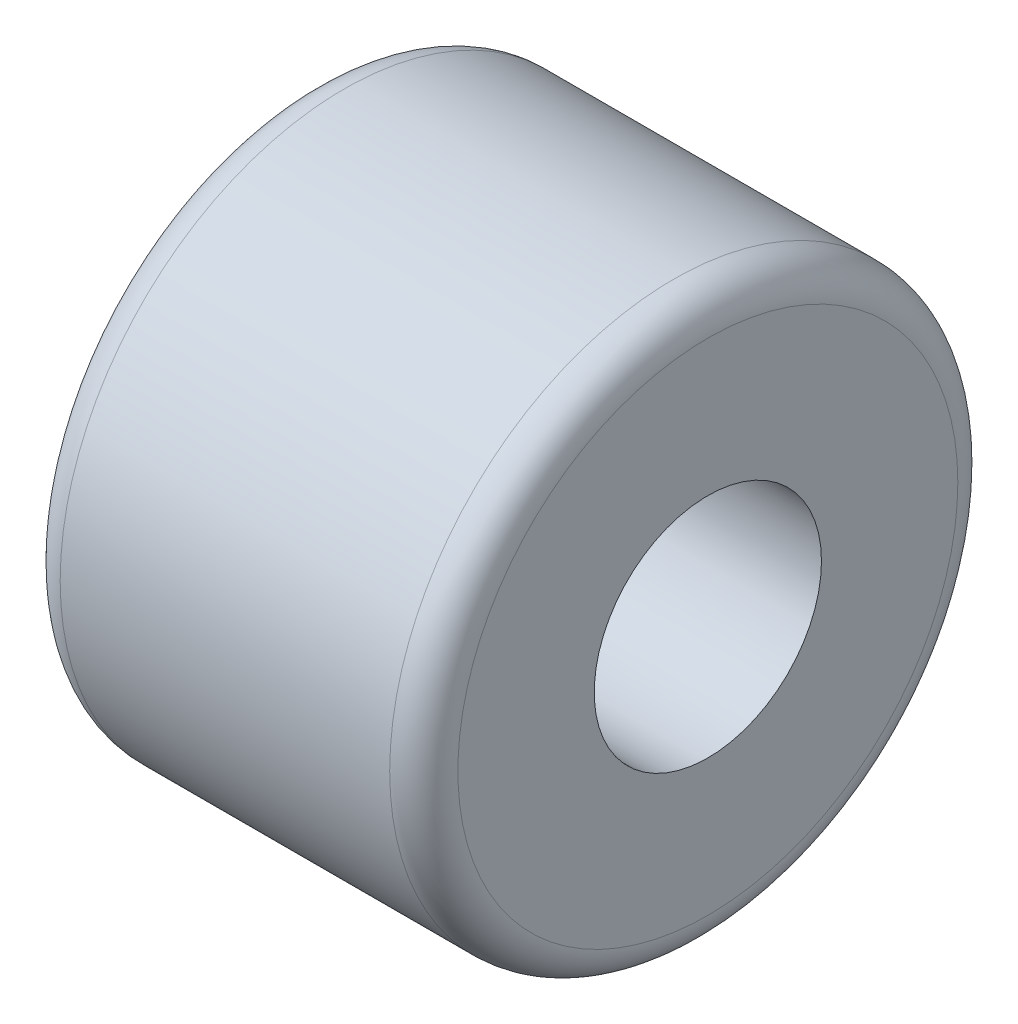
SolidWorks part; units mm, degrees
ref_plane "Front Plane" through (0, 0, 0) normal (1, 0, 0) x (0, 1, 0)
ref_plane "Top Plane" through (0, 0, 0) normal (0, 0, 1) x (0, 1, 0)
ref_plane "Right Plane" through (0, 0, 0) normal (0, 1, 0) x (-1, 0, 0)
sketch "Sketch1" plane through (0, 0, 0) normal (1, 0, 0) x (0, 1, 0)
  circle A0 centre (0, 0) radius 25
  circle A1 centre (0, 0) radius 1.5
  dimension "D1" = 50
  dimension "D2" = 3
extrude "Boss-Extrude1" add sketch "Sketch1" along normal blind 35
sketch "Sketch2" plane through (35, 0, 0) normal (1, 0, 0) x (0, 1, 0)
  circle A0 centre (0, 0) radius 10
  dimension "D1" = 20
extrude "Cut-Extrude1" cut sketch "Sketch2" against normal blind 20
fillet "Fillet2" radius 3 1 edges at (0, 0, -25)
fillet "Fillet3" radius 3 1 edges at (35, 0, -25)
